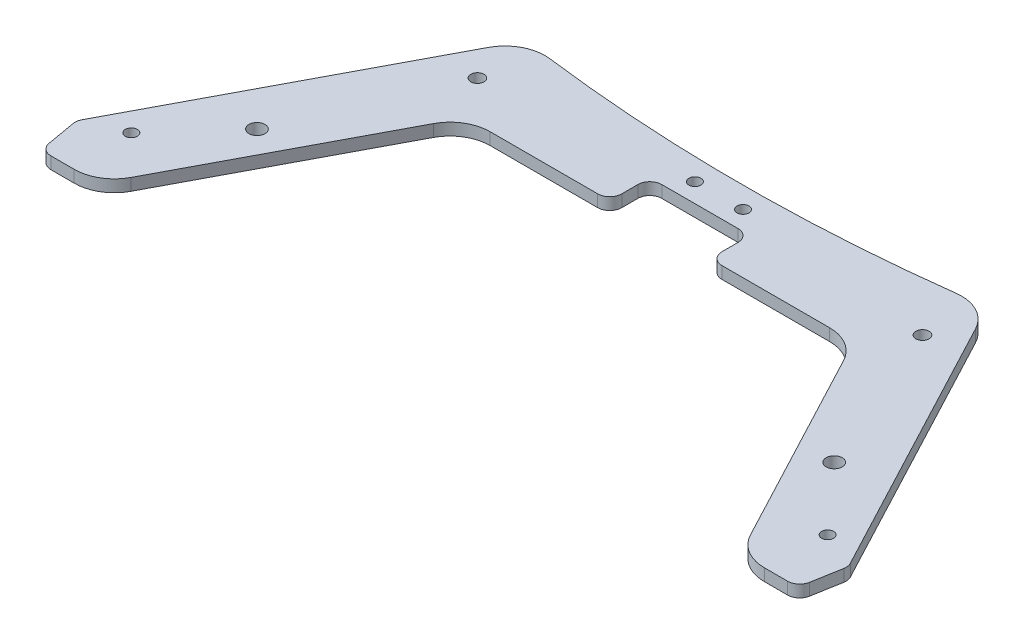
SolidWorks part; units mm, degrees
material "Thornel Mat VMA"
ref_plane "前视基准面" through (0, 0, 0) normal (0, 0, 1) x (1, 0, 0)
ref_plane "上视基准面" through (0, 0, 0) normal (0, 1, 0) x (1, 0, 0)
ref_plane "右视基准面" through (0, 0, 0) normal (1, 0, 0) x (0, 0, -1)
sketch "草图1" plane through (0, 0, 0) normal (0, 1, 0) x (1, 0, 0)
  line L0 (0, 130) -> (0, -202.379) construction
  line L1 (-90, 65) -> (90, 65)
  line L2 (-90, 65) -> (-90, -65)
  line L3 (-90, -65) -> (90, -65)
  line L4 (90, 65) -> (90, -65)
  line L5 (-90, 65) -> (90, -65) construction
  line L6 (-90, -65) -> (90, 65) construction
  line L17 (90, -65) -> (111.2997, 55.7964)
  line L18 (-90, -65) -> (-111.2997, 55.7964)
  circle A7 centre (0, 440) radius 400
  circle A8 centre (-72, -8.5) radius 2
  circle A9 centre (72, -8.5) radius 2
  point P0 (0, 0)
  dimension "D7" = 4
  dimension "D9" = 72
  dimension "D10" = 800
  dimension "D12" = 10
  dimension "D1" = 130
  dimension "D2" = 180
  dimension "D8" = 8.5
  dimension "D11" = 440
extrude "凸台-拉伸1" add sketch "草图1" along normal blind 3
sketch "草图2" plane through (0, 0, 0) normal (0, -1, 0) x (-1, 0, 0)
  line L1 (6, 28.25) -> (-6, 28.25) construction
  line L2 (6, 28.25) -> (6, 34.75) construction
  line L3 (6, 34.75) -> (-6, 34.75) construction
  line L4 (-6, 28.25) -> (-6, 34.75) construction
  line L5 (6, 28.25) -> (-6, 34.75) construction
  line L6 (6, 34.75) -> (-6, 28.25) construction
  circle A0 centre (6, 28.25) radius 1.5
  circle A1 centre (-6, 28.25) radius 1.5
  circle A2 centre (6, 34.75) radius 1.5
  circle A3 centre (-6, 34.75) radius 1.5
  point P0 (0, 31.5)
  dimension "D4" = 3
  dimension "D5" = 3
  dimension "D6" = 3
  dimension "D7" = 3
  dimension "D1" = 6.5
  dimension "D2" = 12
  dimension "D3" = 31.5
extrude "切除-拉伸1" cut sketch "草图2" against normal through all
sketch "草图3" plane through (0, 3, 0) normal (0, 1, 0) x (1, 0, 0)
  line L0 (-90, -65) -> (90, -65) construction
  line L1 (35, 8.5) -> (45, 8.5)
  line L2 (35, 8.5) -> (35, -46.5)
  line L3 (35, -46.5) -> (45, -46.5)
  line L4 (45, 8.5) -> (45, -46.5)
  line L5 (35, 8.5) -> (45, -46.5) construction
  line L6 (35, -46.5) -> (45, 8.5) construction
  line L7 (0, 109.6967) -> (0, -116.804) construction
  line L8 (-35, -46.5) -> (-45, -46.5)
  line L9 (-45, 8.5) -> (-45, -46.5)
  line L10 (-35, 8.5) -> (-45, 8.5)
  line L11 (-35, 8.5) -> (-35, -46.5)
  circle A0 centre (40, -46.5) radius 5
  circle A1 centre (40, 8.5) radius 5
  circle A2 centre (-40, -46.5) radius 5
  circle A3 centre (-40, 8.5) radius 5
  point P0 (40, -19)
  dimension "D1" = 55
  dimension "D2" = 10
  dimension "D3" = 40
  dimension "D4" = 18.5
extrude "切除-拉伸2" cut sketch "草图3" against normal blind 3 contours L11 A3 L9 A2 | A3 L10 | A3 L10 | A2 L8 | A1 L2 A0 L4 | L3 A0 | L3 A0 | L1 A1 | L1 A1
sketch "草图4" plane through (0, 3, 0) normal (0, 1, 0) x (1, 0, 0)
  line L0 (72, -41.5) -> (72, -51.5)
  line L1 (72, -8.5) -> (31.5932, 6.2069)
  circle A0 centre (72, -8.5) radius 33
  circle A1 centre (72, -8.5) radius 43
  line M6 (45, 8.5) -> (45, -46.5)
  line M8 (35, -46.5) -> (35, 8.5)
  dimension "D1" = 66
  dimension "D2" = 86
  dimension "D3" = 110
extrude "切除-拉伸3" cut sketch "草图4" against normal blind 3 contours A1 A0 L1 M8 M6 | L1 A1 M8 | A1 L0 A0 M6
sketch "草图5" plane through (0, 3, 0) normal (0, 1, 0) x (1, 0, 0)
  line L0 (23, 15) -> (23, -55)
  line L1 (23, -55) -> (88, -55)
  line L2 (88, -55) -> (51, 15)
  line L3 (51, 15) -> (23, 15)
  line L4 (0, 95.0959) -> (0, -117.8936) construction
  line L5 (-88, -55) -> (-51, 15)
  line L6 (-23, -55) -> (-88, -55)
  line L7 (-23, 15) -> (-23, -55)
  line L8 (-51, 15) -> (-23, 15)
  dimension "D1" = 70
  dimension "D2" = 65
  dimension "D3" = 15
  dimension "D4" = 28
  dimension "D5" = 23
extrude "切除-拉伸4" cut sketch "草图5" against normal through all
fillet "圆角1" radius 10 8 edges at (-23, 1.5, 55) (-88, 1.5, 55) (88, 1.5, 55) (23, 1.5, 55) (23, 1.5, -15) (51, 1.5, -15) (-51, 1.5, -15) (-23, 1.5, -15)
sketch "草图6" plane through (0, 3, 0) normal (0, 1, 0) x (1, 0, 0)
  line L0 (-90, -65) -> (90, -65) construction
  circle A0 centre (0, -59) radius 1.25
  circle A1 centre (0, -51.5) radius 1.25
  circle A2 centre (0, -44) radius 1.25
  circle A3 centre (0, -36.5) radius 1.25
  circle A4 centre (0, -29) radius 1.25
  circle A5 centre (0, -21.5) radius 1.25
  circle A6 centre (0, -14) radius 1.25
  circle A7 centre (0, -6.5) radius 1.25
  circle A8 centre (0, 1) radius 1.25
  circle A9 centre (0, 8.5) radius 1.25
  circle A10 centre (0, 16) radius 1.25
  dimension "D1" = 2.5
  dimension "D4" = 7.5
  dimension "D2" = 6
  dimension "D3" = 11
extrude "切除-拉伸5" cut sketch "草图6" against normal blind 3
fillet "圆角2" radius 10 2 edges at (90, 1.5, 65) (-90, 1.5, 65)
fillet "圆角3" radius 10 2 edges at (111.2997, 1.5, -55.7964) (-111.2997, 1.5, -55.7964)
sketch "草图7" plane through (0, 3, 0) normal (0, 1, 0) x (1, 0, 0)
  line L0 (-65, 30) -> (-84.3459, -6.6003)
  line L1 (-84.3459, -6.6003) -> (-92.16, 37.7161)
  line L2 (-92.16, 37.7161) -> (-65, 30)
  line L3 (-53.8157, 9.6731) -> (-80.2442, -40.3269) construction
  line L4 (-91.4571, -56.7365) -> (-108.572, 40.3268) construction
  line L5 (0, 179.2069) -> (0, -134.9737) construction
  line L6 (84.3459, -6.6003) -> (92.16, 37.7161)
  line L7 (65, 30) -> (84.3459, -6.6003)
  line L8 (92.16, 37.7161) -> (65, 30)
  dimension "D1" = 78
  dimension "D2" = 65
  dimension "D3" = 30
  dimension "D4" = 45
extrude "切除-拉伸6" cut sketch "草图7" against normal through all
fillet "圆角4" radius 3 6 edges at (84.3459, 1.5, 6.6003) (65, 1.5, -30) (-84.3459, 1.5, 6.6003) (-92.16, 1.5, -37.7161) (-65, 1.5, -30) (92.16, 1.5, -37.7161)
sketch "草图8" plane through (0, 3, 0) normal (0, 1, 0) x (1, 0, 0)
  line L0 (-102, -40) -> (-57.5171, 44.1569)
  line L2 (-80.2581, 1.1333) -> (-66.7312, 26.7247) construction
  line L3 (-102, -40) -> (-80.0714, -40)
  line L4 (-53.8157, 9.6731) -> (-80.2442, -40.3269) construction
  line L5 (-80.0714, -40) -> (-48.3571, 20)
  line L6 (-48.3571, 20) -> (1.9331, 20)
  line L7 (0, -65) -> (0, 0) construction
  line L8 (-81.609, -65) -> (81.609, -65) construction
  line L9 (48.3571, 20) -> (-1.9331, 20)
  line L10 (80.0714, -40) -> (48.3571, 20)
  line L11 (102, -40) -> (80.0714, -40)
  line L12 (102, -40) -> (57.5171, 44.1569)
  arc A0 (-96.316, 51.7691) -> (96.316, 51.7691) centre (0, 440) ccw construction
  circle A1 centre (0, 440) radius 400
  circle A2 centre (0, 0) radius 250
  point P14 (-23.212, 20)
  dimension "D2" = 500
  dimension "D1" = 20
  dimension "D3" = 40
extrude "切除-拉伸7" cut sketch "草图8" against normal blind 10
sketch "草图9" plane through (0, 3, 0) normal (0, 1, 0) x (1, 0, 0)
  line L0 (-48.3571, 20) -> (-80.0714, -40) construction
  line L3 (-94.4082, -40) -> (-80.0714, -40) construction
  line L4 (48.3571, 20) -> (-48.3571, 20) construction
  line L5 (0, 109.3243) -> (0, -74.9027) construction
  circle A0 centre (-55.5135, 30) radius 1.65
  circle A1 centre (-86.8472, -25) radius 1.5
  circle A2 centre (86.8472, -25) radius 1.5
  circle A3 centre (55.5135, 30) radius 1.65
  dimension "D1" = 3.3
  dimension "D2" = 3
  dimension "D6" = 11
  dimension "D3" = 13
  dimension "D4" = 15
  dimension "D5" = 10
extrude "切除-拉伸8" cut sketch "草图9" against normal through all
fillet "圆角5" radius 10 6 edges at (-80.0714, 1.5, 40) (-48.3571, 1.5, -20) (48.3571, 1.5, -20) (80.0714, 1.5, 40) (57.5171, 1.5, -44.1569) (-57.5171, 1.5, -44.1569)
sketch "草图10" plane through (0, 3, 0) normal (0, 1, 0) x (1, 0, 0)
  line L0 (42.3319, 20) -> (-42.3319, 20) construction
  line L1 (-12.5, 30) -> (12.5, 30)
  line L2 (-12.5, 30) -> (-12.5, 10)
  line L3 (-12.5, 10) -> (12.5, 10)
  line L4 (12.5, 30) -> (12.5, 10)
  line L5 (-12.5, 30) -> (12.5, 10) construction
  line L6 (-12.5, 10) -> (12.5, 30) construction
  point P0 (0, 20)
  dimension "D1" = 20
  dimension "D2" = 25
extrude "切除-拉伸9" cut sketch "草图10" against normal through all
fillet "圆角6" radius 3 8 edges at (94.4082, 1.5, 40) (96.3072, 1.5, 29.2299) (-96.3072, 1.5, 29.2299) (-94.4082, 1.5, 40) (-12.5, 1.5, -30) (12.5, 1.5, -30) (12.5, 1.5, -20) (-12.5, 1.5, -20)
